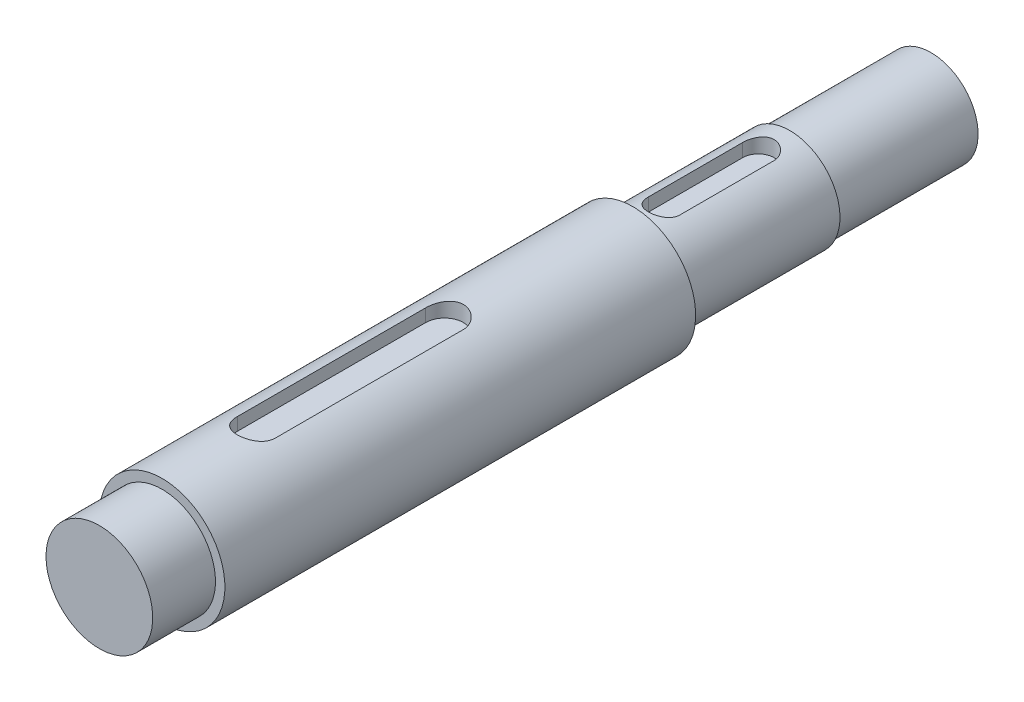
SolidWorks part; units mm, degrees
ref_plane "Front Plane" through (0, 0, 0) normal (0, 0, 1) x (1, 0, 0)
ref_plane "Top Plane" through (0, 0, 0) normal (0, 1, 0) x (1, 0, 0)
ref_plane "Right Plane" through (0, 0, 0) normal (1, 0, 0) x (0, 0, -1)
sketch "Sketch1" plane through (0, 0, 0) normal (0, 1, 0) x (1, 0, 0)
  line L0 (0, 0) -> (0, -265)
  line L3 (15, -45) -> (16, -45)
  line L4 (16, -45) -> (16, -95)
  line L7 (16, -95) -> (20, -95)
  line L8 (20, -95) -> (20, -245)
  line L9 (20, -245) -> (17, -245)
  line L10 (17, -245) -> (17, -265)
  line L11 (17, -265) -> (0, -265)
  line L12 (15, -45) -> (15, 0)
  line L13 (15, 0) -> (0, 0)
  point P3 (0, 0)
  point P4 (0, 0)
  point P8 (0, 0)
  dimension "D1" = 17
  dimension "D2" = 265
  dimension "D3" = 50
  dimension "D4" = 16
  dimension "D5" = 150
  dimension "D6" = 45
  dimension "D7" = 1
  dimension "D8" = 20
revolve "Revolve1" add sketch "Sketch1" angle 360 about L0
sketch "Sketch2" plane through (-4.4668, 29.5948, 45) normal (0, 0, -1) x (-1, 0, 0)
  line L0 (-4.4668, -13.5948) -> (-4.4668, -29.5948) construction
  line L1 (-4.4668, -29.5948) -> (-4.4668, -13.5948) construction
  circle A0 centre (-4.4668, -29.5948) radius 16 construction
  circle A2 centre (-4.4668, -29.5948) radius 16
  dimension "Angle from vertical" = 360
ref_plane "Plane1" through (0, 16, 45) normal (0, -1, 0) x (-1, 0, 0)
sketch "Sketch3" plane through (2.2334, 16, 45) normal (0, -1, 0) x (0, 0, -1)
  line L0 (-10, -2.2334) -> (-40, -2.2334) construction
  line L1 (-10, 2.7666) -> (-40, 2.7666)
  line L2 (-10, -7.2334) -> (-40, -7.2334)
  arc A0 (-10, 2.7666) -> (-10, -7.2334) centre (-10, -2.2334) cw
  arc A1 (-40, 2.7666) -> (-40, -7.2334) centre (-40, -2.2334) ccw
  dimension "Keyway width" = 10
  dimension "Distance from end face" = 10
  dimension "Length of slot" = 30
extrude "Cut-Extrude1" cut sketch "Sketch3" along normal blind 5
other "keyway (bs 4235 - part i)<1>"
sketch "Sketch21" plane through (-2.2756, 37.0318, 245) normal (0, 0, 1) x (1, 0, 0)
  line L0 (2.2756, -17.0318) -> (2.2756, -37.0318) construction
  line L1 (2.2756, -37.0318) -> (2.2756, -17.0318) construction
  circle A0 centre (2.2756, -37.0318) radius 20 construction
  circle A2 centre (2.2756, -37.0318) radius 20
  dimension "Angle from vertical" = 0
ref_plane "Plane11" through (0, 20, 245) normal (0, -1, 0) x (-1, 0, 0)
sketch "Sketch31" plane through (1.1378, 20, 245) normal (0, -1, 0) x (0, 0, 1)
  line L0 (-30, 1.1378) -> (-90, 1.1378) construction
  line L1 (-30, 7.1378) -> (-90, 7.1378)
  line L2 (-30, -4.8622) -> (-90, -4.8622)
  arc A0 (-30, 7.1378) -> (-30, -4.8622) centre (-30, 1.1378) cw
  arc A1 (-90, 7.1378) -> (-90, -4.8622) centre (-90, 1.1378) ccw
  dimension "Keyway width" = 12
  dimension "Distance from end face" = 30
  dimension "Length of slot" = 60
extrude "Cut-Extrude11" cut sketch "Sketch31" along normal blind 5
other "keyway (bs 4235 - part i)<2>"
